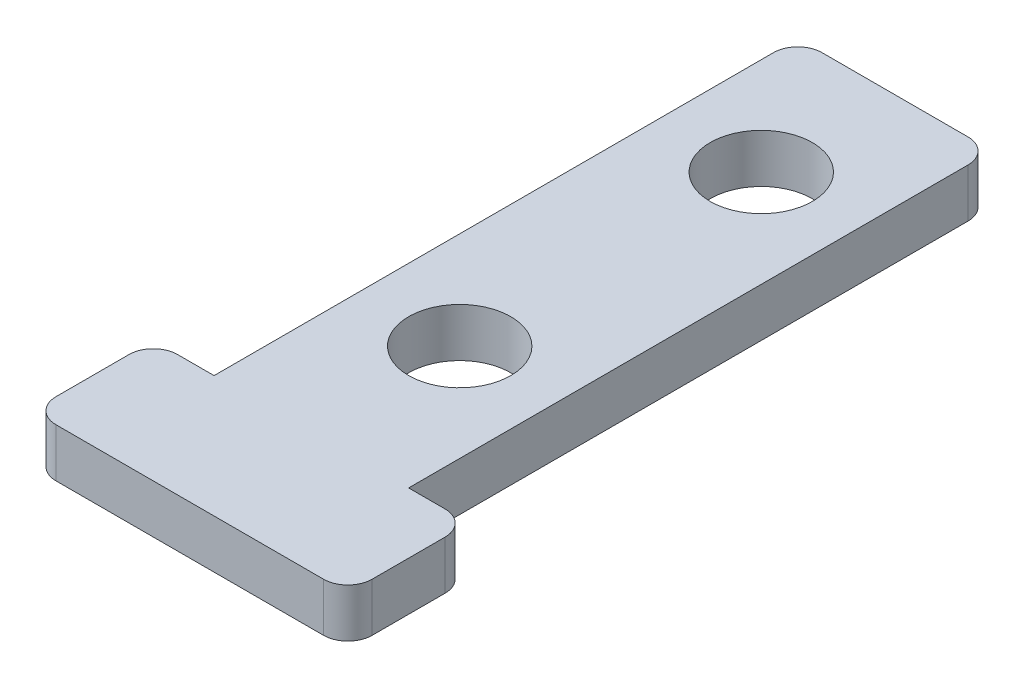
SolidWorks part; units mm, degrees
ref_plane "Front Plane" through (0, 0, 0) normal (0, 0, 1) x (1, 0, 0)
ref_plane "Top Plane" through (0, 0, 0) normal (0, 1, 0) x (1, 0, 0)
ref_plane "Right Plane" through (0, 0, 0) normal (1, 0, 0) x (0, 0, -1)
sketch "Sketch1" plane through (0, 0, 0) normal (0, 1, 0) x (1, 0, 0)
  line L0 (-6.5, 0) -> (6.5, 0)
  line L1 (-6.5, 0) -> (-6.5, 5)
  line L2 (-6.5, 5) -> (-4, 5)
  line L3 (6.5, 0) -> (6.5, 5)
  line L4 (6.5, 5) -> (4, 5)
  line L5 (-4, 5) -> (-4, 29)
  line L7 (-4, 29) -> (4, 29)
  line L8 (4, 5) -> (4, 29)
  circle A1 centre (0, 11.1) radius 2.1
  circle A2 centre (0, 23.5) radius 2.1
  point P4 (0, 0)
  dimension "D7" = 5.5
  dimension "D1" = 13
  dimension "D2" = 5
  dimension "D3" = 2.5
  dimension "D4" = 2.5
  dimension "D5" = 24
  dimension "D6" = 12.4
extrude "Boss-Extrude1" add sketch "Sketch1" along normal blind 2
fillet "Fillet1" radius 1 1 edges at (6.5, 1, 0)
fillet "Fillet2" radius 1 1 edges at (6.5, 1, -5)
fillet "Fillet3" radius 1 1 edges at (-6.5, 1, 0)
fillet "Fillet4" radius 1 1 edges at (-6.5, 1, -5)
fillet "Fillet5" radius 1 1 edges at (-4, 1, -29)
fillet "Fillet6" radius 1 1 edges at (4, 1, -29)
